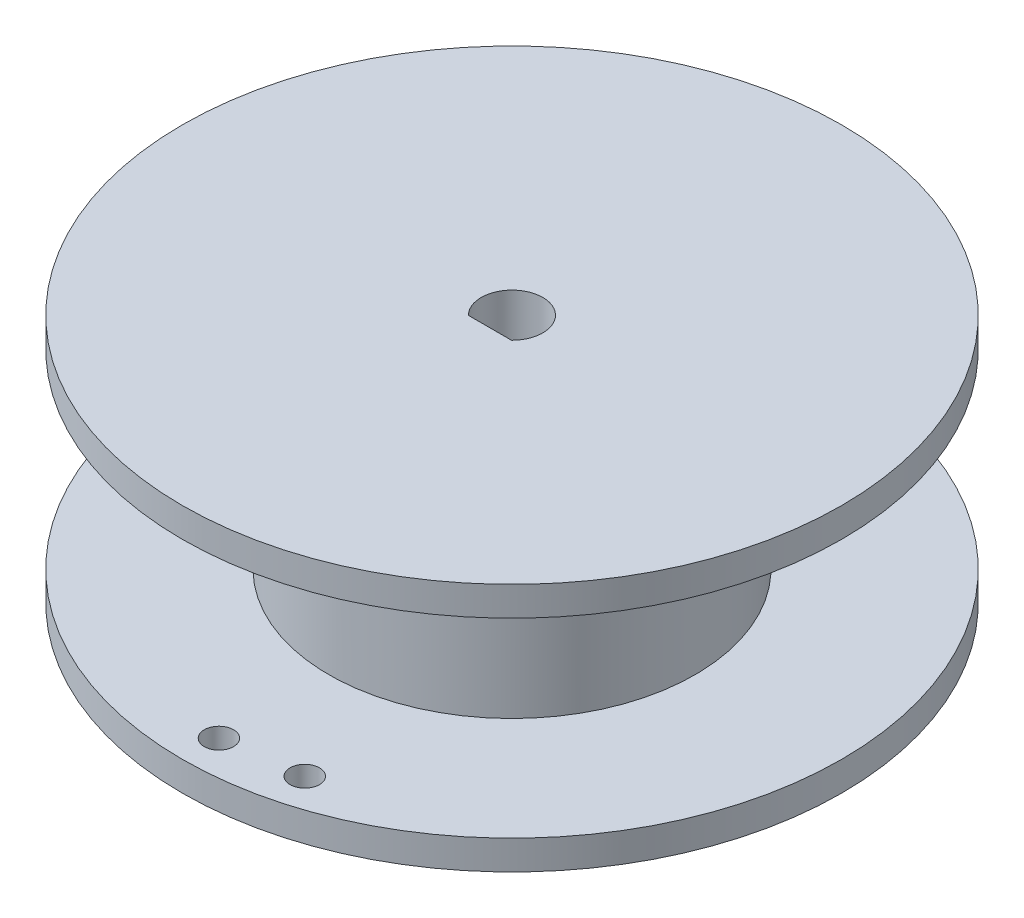
SolidWorks part; units mm, degrees
ref_plane "前视基准面" through (0, 0, 0) normal (0, 0, 1) x (1, 0, 0)
ref_plane "上视基准面" through (0, 0, 0) normal (0, 1, 0) x (1, 0, 0)
ref_plane "右视基准面" through (0, 0, 0) normal (1, 0, 0) x (0, 0, -1)
other "Configuration Table"
sketch "草图1" plane through (0, 0, 0) normal (0, 1, 0) x (1, 0, 0)
  line L0 (-1.4697, -1.5) -> (1.4697, -1.5)
  circle A0 centre (0, 0) radius 12.5
  arc A1 (1.4697, -1.5) -> (-1.4697, -1.5) centre (0, 0) ccw
  point P6 (0, -1.5)
  dimension "D1" = 25
  dimension "D2" = 4.2
  dimension "D3" = 1.5
extrude "凸台-拉伸1" add sketch "草图1" along normal blind 15
sketch "草图2" plane through (0, 0, 0) normal (0, -1, 0) x (1, 0, 0)
  line L0 (-1.4697, 1.5) -> (1.4697, 1.5) construction
  line L1 (-1.4697, 1.5) -> (1.4697, 1.5)
  circle A0 centre (0, 20) radius 1
  arc A1 (-1.4697, 1.5) -> (1.4697, 1.5) centre (0, 0) ccw construction
  circle A2 centre (0, 0) radius 22.5
  circle A3 centre (0, 0) radius 22.5
  arc A4 (-1.4697, 1.5) -> (1.4697, 1.5) centre (0, 0) ccw
  circle A5 centre (5.1764, 19.3185) radius 1
  point P8 (0, 0)
  point P9 (0, 20)
  point P14 (0, 0)
  dimension "D2" = 20
  dimension "D3" = 2
  dimension "D1" = 10
  dimension "D4" = 2
extrude "凸台-拉伸2" add sketch "草图2" against normal blind 2
sketch "草图3" plane through (0, 15, 0) normal (0, 1, 0) x (1, 0, 0)
  line L1 (-1.4697, -1.5) -> (1.4697, -1.5)
  line L2 (-1.4697, -1.5) -> (1.4697, -1.5)
  circle A0 centre (0, 0) radius 22.5
  circle A1 centre (0, 0) radius 12.5 construction
  arc A5 (1.4697, -1.5) -> (-1.4697, -1.5) centre (0, 0) ccw
  arc A6 (1.4697, -1.5) -> (-1.4697, -1.5) centre (0, 0) ccw
  dimension "D3" = 10
  dimension "D2" = 0
extrude "凸台-拉伸3" add sketch "草图3" along normal blind 2
